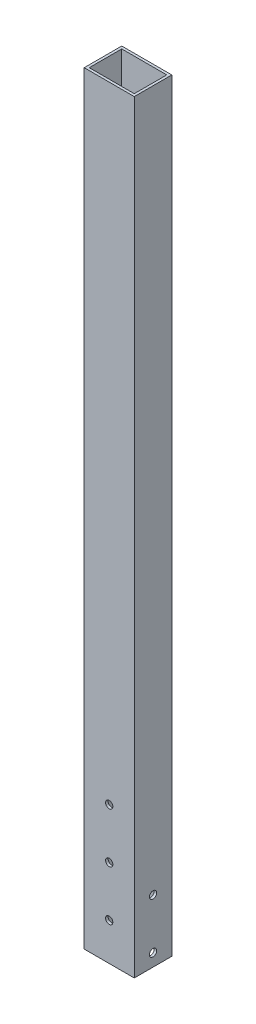
SolidWorks part; units mm, degrees
material "Thornel Mat VMA"
ref_plane "前视基准面" through (0, 0, 0) normal (0, 0, 1) x (1, 0, 0)
ref_plane "上视基准面" through (0, 0, 0) normal (0, 1, 0) x (1, 0, 0)
ref_plane "右视基准面" through (0, 0, 0) normal (1, 0, 0) x (0, 0, -1)
sketch "草图1" plane through (0, 0, 0) normal (0, 1, 0) x (1, 0, 0)
  line L1 (-10, -7.5) -> (10, -7.5)
  line L2 (-10, -7.5) -> (-10, 7.5)
  line L3 (-10, 7.5) -> (10, 7.5)
  line L4 (10, -7.5) -> (10, 7.5)
  line L5 (-10, -7.5) -> (10, 7.5) construction
  line L6 (-10, 7.5) -> (10, -7.5) construction
  point P0 (0, 0)
  dimension "D1" = 20
  dimension "D2" = 15
extrude "拉伸-薄壁1" add sketch "草图1" along normal blind 305 thin thin type one direction reverse wall 1
sketch "草图2" plane through (10, 0, 0) normal (1, 0, 0) x (0, 0, -1)
  line L0 (0, 0) -> (0, 305) construction
  line L1 (-7.5, 305) -> (7.5, 305) construction
  line L2 (-7.5, 0) -> (7.5, 0) construction
  circle A0 centre (0, 5) radius 1.45
  circle A1 centre (0, 25) radius 1.45
  dimension "D1" = 2.9
  dimension "D4" = 2.9
  dimension "D2" = 5
  dimension "D3" = 20
extrude "切除-拉伸1" cut sketch "草图2" against normal through all
sketch "草图3" plane through (0, 0, -7.5) normal (0, 0, -1) x (-1, 0, 0)
  line L0 (0, 0) -> (0, 305) construction
  line L1 (-10, 305) -> (10, 305) construction
  line L2 (-10, 0) -> (10, 0) construction
  circle A0 centre (0, 15) radius 1.45
  circle A1 centre (0, 35) radius 1.45
  circle A2 centre (0, 55) radius 1.45
  dimension "D1" = 2.9
  dimension "D2" = 15
  dimension "D3" = 20
  dimension "D4" = 20
extrude "切除-拉伸2" cut sketch "草图3" against normal through all
